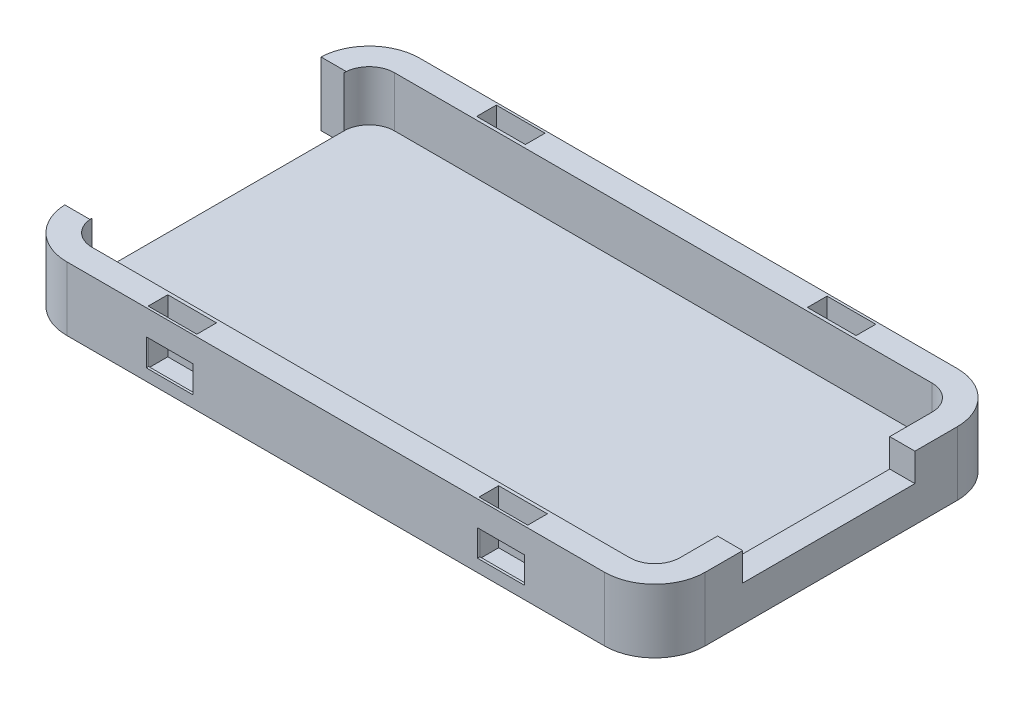
SolidWorks part; units mm, degrees
ref_plane "前视基准面" through (0, 0, 0) normal (0, 0, 1) x (1, 0, 0)
ref_plane "上视基准面" through (0, 0, 0) normal (0, 1, 0) x (1, 0, 0)
ref_plane "右视基准面" through (0, 0, 0) normal (1, 0, 0) x (0, 0, -1)
sketch "草图1" plane through (0, 0, 0) normal (0, 1, 0) x (1, 0, 0)
  line L0 (-16, 10.5) -> (16, 10.5)
  line L1 (-16, 9) -> (16, 9)
  line L2 (-17.5, 7.5) -> (-17.5, -7.5)
  line L3 (-16, -9) -> (16, -9)
  line L4 (17.5, 7.5) -> (17.5, -7.5)
  line L5 (-17.5, 9) -> (17.5, -9) construction
  line L6 (-17.5, -9) -> (17.5, 9) construction
  line L7 (19, 7.5) -> (19, -7.5)
  line L8 (-16, -10.5) -> (16, -10.5)
  line L9 (-19, 7.5) -> (-19, -7.5)
  line L10 (-18.186, 7.6661) -> (16.814, -10.3339)
  line L11 (-16.814, -10.3339) -> (18.186, 7.6661)
  arc A0 (-17.5, -7.5) -> (-16, -9) centre (-16, -7.5) ccw
  arc A1 (16, -9) -> (17.5, -7.5) centre (16, -7.5) ccw
  arc A2 (17.5, 7.5) -> (16, 9) centre (16, 7.5) ccw
  arc A3 (-16, 9) -> (-17.5, 7.5) centre (-16, 7.5) ccw
  arc A4 (19, 7.5) -> (16, 10.5) centre (16, 7.5) ccw
  arc A5 (16, -10.5) -> (19, -7.5) centre (16, -7.5) ccw
  arc A6 (-19, -7.5) -> (-16, -10.5) centre (-16, -7.5) ccw
  arc A7 (-16, 10.5) -> (-19, 7.5) centre (-16, 7.5) ccw
  point P0 (0, 0)
  dimension "D3" = 1.5
  dimension "D1" = 35
  dimension "D2" = 18
  dimension "D4" = 1.5
extrude "凸台-拉伸3" add sketch "草图1" along normal blind 3
sketch "草图3" plane through (0, 0, 0) normal (0, -1, 0) x (1, 0, 0)
  line L0 (-16, 10.5) -> (16, 10.5) construction
  line L1 (-16, 10.5) -> (16, 10.5)
  line L2 (-19, -7.5) -> (-19, 7.5) construction
  line L3 (-16, -10.5) -> (16, -10.5) construction
  line L4 (19, -7.5) -> (19, 7.5) construction
  line L5 (-19, -7.5) -> (-19, 7.5)
  line L6 (-16, -10.5) -> (16, -10.5)
  line L7 (19, -7.5) -> (19, 7.5)
  arc A0 (-16, 10.5) -> (-19, 7.5) centre (-16, 7.5) ccw construction
  arc A1 (-16, 10.5) -> (-19, 7.5) centre (-16, 7.5) ccw
  arc A2 (-19, -7.5) -> (-16, -10.5) centre (-16, -7.5) ccw construction
  arc A3 (16, -10.5) -> (19, -7.5) centre (16, -7.5) ccw construction
  arc A4 (19, 7.5) -> (16, 10.5) centre (16, 7.5) ccw construction
  arc A5 (-19, -7.5) -> (-16, -10.5) centre (-16, -7.5) ccw
  arc A6 (16, -10.5) -> (19, -7.5) centre (16, -7.5) ccw
  arc A7 (19, 7.5) -> (16, 10.5) centre (16, 7.5) ccw
extrude "凸台-拉伸4" add sketch "草图3" along normal blind 0.8
sketch "草图4" plane through (0, 3, 0) normal (0, 1, 0) x (1, 0, 0)
  line L0 (-23.2798, 0) -> (26.7521, 0) construction
  line L1 (-17.5, 7.625) -> (-20.5, 7.625)
  line L3 (-17.5, 7.5) -> (-17.5, -7.5) construction
  line L4 (-20.5, 7.625) -> (-20.5, -7.625)
  line L5 (-20.5, -7.625) -> (-17.5, -7.625)
  line L6 (-17.5, -7.625) -> (-17.5, 7.625)
  dimension "D1" = 15.25
  dimension "D2" = 3
extrude "切除-拉伸1" cut sketch "草图4" against normal blind 4
sketch "草图5" plane through (19, 0, 0) normal (1, 0, 0) x (0, 0, -1)
  line L0 (7.5, 3) -> (-7.5, 3) construction
  line L9 (-5.269, 1.6813) -> (4.981, 1.6813)
  line L10 (4.981, 1.6813) -> (4.981, 4.9713)
  line L11 (4.981, 4.9713) -> (-5.269, 4.9713)
  line L12 (-5.269, 4.9713) -> (-5.269, 1.6813)
  line L13 (-5.269, 1.3259) -> (4.981, 1.3259)
  line L14 (4.981, 1.3259) -> (4.981, 4.9713)
  line L15 (4.981, 4.9713) -> (-5.269, 4.9713)
  line L16 (-5.269, 4.9713) -> (-5.269, 1.3259)
  point P0 (0, 3)
  dimension "D1" = 0
extrude "切除-拉伸2" cut sketch "草图5" against normal blind 3
sketch "草图6" plane through (0, 3, 0) normal (0, 1, 0) x (1, 0, 0)
  line L0 (8.3924, -10.3579) -> (11.292, -10.3579)
  line L1 (-11.2978, -10.3618) -> (-8.3982, -10.3618)
  line L2 (-11.2978, -10.3618) -> (-11.2978, -9.1924)
  line L3 (-11.2978, -9.1924) -> (-8.3982, -9.1924)
  line L4 (-8.3982, -10.3618) -> (-8.3982, -9.1924)
  line L5 (8.3924, -10.3579) -> (8.3924, -9.1885)
  line L6 (8.3924, -9.1885) -> (11.292, -9.1885)
  line L7 (11.292, -10.3579) -> (11.292, -9.1885)
  line L8 (0, 10.5) -> (0, -10.5) construction
  line L9 (-16, 10.5) -> (16, 10.5) construction
  line L10 (16, -10.5) -> (-16, -10.5) construction
  line L11 (0, 0) -> (23.3741, 0) construction
  line L12 (11.292, 10.3579) -> (11.292, 9.1885)
  line L13 (8.3924, 9.1885) -> (11.292, 9.1885)
  line L14 (8.3924, 10.3579) -> (8.3924, 9.1885)
  line L15 (-8.3982, 10.3618) -> (-8.3982, 9.1924)
  line L16 (-11.2978, 9.1924) -> (-8.3982, 9.1924)
  line L17 (-11.2978, 10.3618) -> (-11.2978, 9.1924)
  line L18 (-11.2978, 10.3618) -> (-8.3982, 10.3618)
  line L19 (8.3924, 10.3579) -> (11.292, 10.3579)
extrude "切除-拉伸3" cut sketch "草图6" against normal blind 3.2
sketch "草图7" plane through (0, 0, -10.5) normal (0, 0, -1) x (-1, 0, 0)
  line L1 (8.4845, 1.5361) -> (11.2703, 1.5361)
  line L2 (8.4845, 1.5361) -> (8.4845, -0.1011)
  line L3 (8.4845, -0.1011) -> (11.2703, -0.1011)
  line L4 (11.2703, 1.5361) -> (11.2703, -0.1011)
  line L5 (-11.2416, 1.5361) -> (-8.4318, 1.5361)
  line L6 (-11.2416, 1.5361) -> (-11.2416, -0.0478)
  line L7 (-11.2416, -0.0478) -> (-8.4318, -0.0478)
  line L8 (-8.4318, 1.5361) -> (-8.4318, -0.0478)
extrude "切除-拉伸5" cut sketch "草图7" against normal up to surface (0.1421 mm away) up to face at (9.8422, 1.4, -10.3579)
sketch "草图8" plane through (0, 0, 10.5) normal (0, 0, 1) x (1, 0, 0)
  line L1 (11.2369, -0.055) -> (8.4433, -0.055)
  line L2 (11.2369, -0.055) -> (11.2369, 1.515)
  line L3 (11.2369, 1.515) -> (8.4433, 1.515)
  line L4 (8.4433, -0.055) -> (8.4433, 1.515)
  line L5 (-8.4855, 1.5) -> (-11.2706, 1.5)
  line L6 (-8.4855, 1.5) -> (-8.4855, -0.1027)
  line L7 (-8.4855, -0.1027) -> (-11.2706, -0.1027)
  line L8 (-11.2706, 1.5) -> (-11.2706, -0.1027)
extrude "切除-拉伸6" cut sketch "草图8" against normal up to surface (0.4637 mm away)
